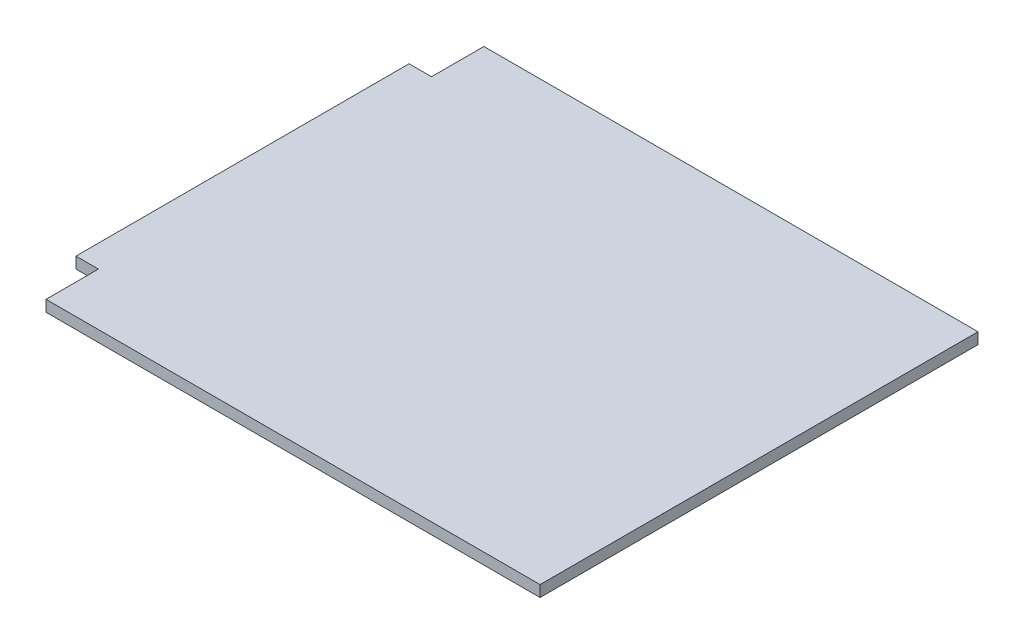
SolidWorks part; units mm, degrees
material "Balsa"
ref_plane "Front Plane" through (0, 0, 0) normal (0, 0, 1) x (1, 0, 0)
ref_plane "Top Plane" through (0, 0, 0) normal (0, 1, 0) x (1, 0, 0)
ref_plane "Right Plane" through (0, 0, 0) normal (1, 0, 0) x (0, 0, -1)
sketch "Sketch1" plane through (0, 0, 0) normal (0, 1, 0) x (1, 0, 0)
  line L0 (0, 0) -> (38.1, 0)
  line L1 (38.1, 0) -> (38.1, 88.9)
  line L2 (38.1, 88.9) -> (876.3, 88.9)
  line L3 (876.3, 88.9) -> (876.3, -654.05)
  line L4 (876.3, -654.05) -> (38.1, -654.05)
  line L5 (38.1, -654.05) -> (38.1, -565.15)
  line L6 (38.1, -565.15) -> (0, -565.15)
  line L7 (0, -565.15) -> (0, 0)
  dimension "D1" = 838.2
  dimension "D2" = 38.1
  dimension "D3" = 88.9
  dimension "D4" = 38.1
  dimension "D5" = 88.9
  dimension "D6" = 565.15
extrude "Boss-Extrude1" add sketch "Sketch1" along normal blind 19.05
